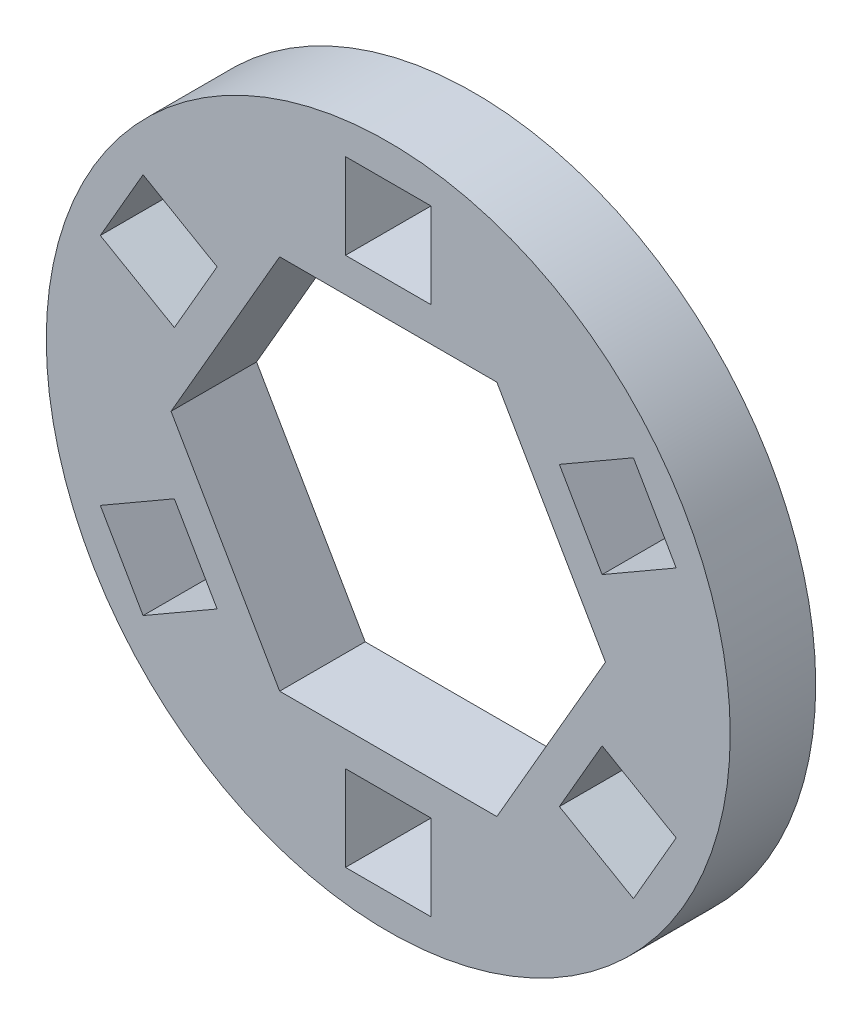
SolidWorks part; units mm, degrees
ref_plane "Front Plane" through (0, 0, 0) normal (0, 0, 1) x (1, 0, 0)
ref_plane "Top Plane" through (0, 0, 0) normal (0, 1, 0) x (1, 0, 0)
ref_plane "Right Plane" through (0, 0, 0) normal (1, 0, 0) x (0, 0, -1)
sketch "Sketch1" plane through (0, 0, 0) normal (0, 0, 1) x (1, 0, 0)
  line L0 (-20, 0) -> (20, 0) construction
  line L1 (12.7017, 0) -> (6.3509, 11)
  line L2 (6.3509, 11) -> (-6.3509, 11)
  line L3 (-6.3509, 11) -> (-12.7017, 0)
  line L4 (-12.7017, 0) -> (-6.3509, -11)
  line L5 (-6.3509, -11) -> (6.3509, -11)
  line L6 (6.3509, -11) -> (12.7017, 0)
  line L7 (-2.5, 18) -> (2.5, 18)
  line L8 (-2.5, 18) -> (-2.5, 13)
  line L9 (-2.5, 13) -> (2.5, 13)
  line L10 (2.5, 18) -> (2.5, 13)
  line L23 (0, 20) -> (0, -20) construction
  line L24 (16.8385, 6.8349) -> (12.5083, 4.3349)
  line L25 (10.0083, 8.6651) -> (12.5083, 4.3349)
  line L26 (14.3385, 11.1651) -> (10.0083, 8.6651)
  line L27 (14.3385, 11.1651) -> (16.8385, 6.8349)
  line L28 (14.3385, -11.1651) -> (10.0083, -8.6651)
  line L29 (12.5083, -4.3349) -> (10.0083, -8.6651)
  line L30 (16.8385, -6.8349) -> (12.5083, -4.3349)
  line L31 (16.8385, -6.8349) -> (14.3385, -11.1651)
  line L32 (-2.5, -18) -> (-2.5, -13)
  line L33 (2.5, -13) -> (-2.5, -13)
  line L34 (2.5, -18) -> (2.5, -13)
  line L35 (2.5, -18) -> (-2.5, -18)
  line L36 (-16.8385, -6.8349) -> (-12.5083, -4.3349)
  line L37 (-10.0083, -8.6651) -> (-12.5083, -4.3349)
  line L38 (-14.3385, -11.1651) -> (-10.0083, -8.6651)
  line L39 (-14.3385, -11.1651) -> (-16.8385, -6.8349)
  line L40 (-14.3385, 11.1651) -> (-10.0083, 8.6651)
  line L41 (-12.5083, 4.3349) -> (-10.0083, 8.6651)
  line L42 (-16.8385, 6.8349) -> (-12.5083, 4.3349)
  line L43 (-16.8385, 6.8349) -> (-14.3385, 11.1651)
  circle A0 centre (0, 0) radius 11 construction
  circle A1 centre (0, 0) radius 20
  point P40 (0, 0)
  dimension "D2" = 40
  dimension "D1" = 22
  dimension "D3" = 5
  dimension "D4" = 5
  dimension "D5" = 13
  dimension "D6" = 6
extrude "Boss-Extrude1" add sketch "Sketch1" along normal blind 5
